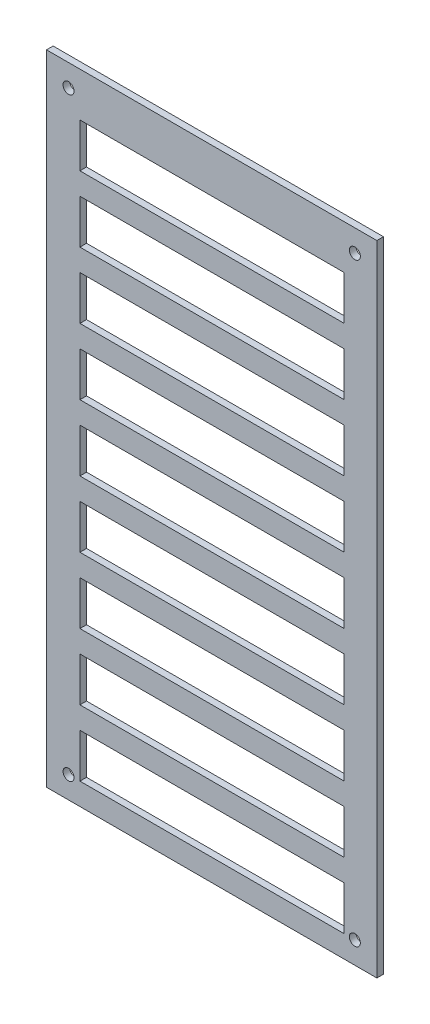
SolidWorks part; units mm, degrees
ref_plane "前视基准面" through (0, 0, 0) normal (0, 0, 1) x (1, 0, 0)
ref_plane "上视基准面" through (0, 0, 0) normal (0, 1, 0) x (1, 0, 0)
ref_plane "右视基准面" through (0, 0, 0) normal (1, 0, 0) x (0, 0, -1)
other "Configuration Table"
sketch "草图1" plane through (0, 0, 0) normal (0, 0, 1) x (1, 0, 0)
  line L1 (-25.1448, 49.8785) -> (124.8552, 49.8785)
  line L2 (-25.1448, 49.8785) -> (-25.1448, -240.1215)
  line L3 (-25.1448, -240.1215) -> (124.8552, -240.1215)
  line L4 (124.8552, 49.8785) -> (124.8552, -240.1215)
  dimension "D1" = 290
  dimension "D2" = 150
extrude "凸台-拉伸1" add sketch "草图1" along normal blind 3
sketch "草图2" plane through (0, 0, 3) normal (0, 0, 1) x (1, 0, 0)
  line L0 (124.8552, 49.8785) -> (-25.1448, 49.8785) construction
  line L1 (124.8552, -240.1215) -> (124.8552, 49.8785) construction
  line L2 (-25.1448, -240.1215) -> (124.8552, -240.1215) construction
  line L3 (-25.1448, 49.8785) -> (-25.1448, -240.1215) construction
  circle A0 centre (114.8552, 39.8785) radius 2.5
  circle A1 centre (114.8552, -230.1215) radius 2.5
  circle A2 centre (-15.1448, 39.8785) radius 2.5
  circle A3 centre (-15.1448, -230.1215) radius 2.5
  dimension "D1" = 10
  dimension "D2" = 10
  dimension "D3" = 10
  dimension "D4" = 10
  dimension "D5" = 10
  dimension "D6" = 10
  dimension "D7" = 10
  dimension "D8" = 10
extrude "切除-拉伸1" cut sketch "草图2" against normal blind 3
sketch "草图3" plane through (0, 0, 3) normal (0, 0, 1) x (1, 0, 0)
  line L0 (124.8552, 49.8785) -> (-25.1448, 49.8785) construction
  line L1 (-9.9798, 29.8785) -> (110.0202, 29.8785)
  line L2 (-9.9798, 29.8785) -> (-9.9798, 9.8785)
  line L3 (-9.9798, 9.8785) -> (110.0202, 9.8785)
  line L4 (110.0202, 29.8785) -> (110.0202, 9.8785)
  dimension "D1" = 20
  dimension "D2" = 120
  dimension "D3" = 20
extrude "切除-拉伸2" cut sketch "草图3" against normal blind 3
pattern_linear "阵列(线性)1" count 9 spacing 30 along (0, -1, 0) of "切除-拉伸2"
